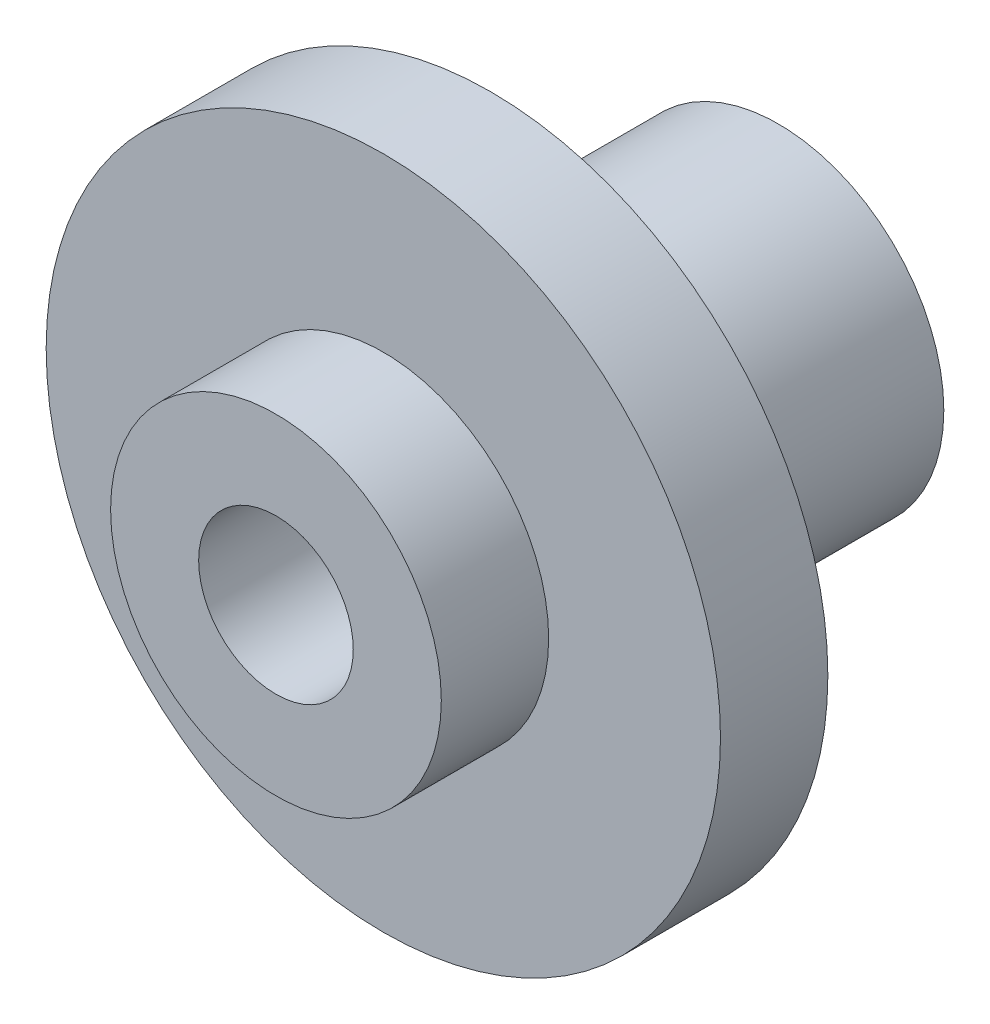
SolidWorks part; units mm, degrees
ref_plane "Front Plane" through (0, 0, 0) normal (0, 0, 1) x (1, 0, 0)
ref_plane "Top Plane" through (0, 0, 0) normal (0, 1, 0) x (1, 0, 0)
ref_plane "Right Plane" through (0, 0, 0) normal (1, 0, 0) x (0, 0, -1)
sketch "Sketch1" plane through (0, 0, 0) normal (0, 0, 1) x (1, 0, 0)
  circle A0 centre (0, 0) radius 3.9878
  dimension "D1" = 7.9756
extrude "Boss-Extrude1" add sketch "Sketch1" along normal blind 1.27
sketch "Sketch2" plane through (0, 0, 1.27) normal (0, 0, 1) x (1, 0, 0)
  circle A0 centre (0, 0) radius 1.9558
  circle A1 centre (0, 0) radius 0.9144
  dimension "D1" = 3.9116
  dimension "D2" = 1.8288
extrude "Boss-Extrude2" add sketch "Sketch2" along normal blind 1.27
sketch "Sketch3" plane through (0, 0, 0) normal (0, 0, -1) x (-1, 0, 0)
  circle A0 centre (0, 0) radius 1.9558
  dimension "D1" = 3.9116
extrude "Boss-Extrude3" add sketch "Sketch3" along normal blind 3.4036
sketch "Sketch4" plane through (0, 0, -3.4036) normal (0, 0, -1) x (-1, 0, 0)
  circle A0 centre (0, 0) radius 0.9144
  dimension "D1" = 1.8288
extrude "Cut-Extrude1" cut sketch "Sketch4" against normal through all
sketch "Sketch5" plane through (0, 0, -3.4036) normal (0, 0, -1) x (-1, 0, 0)
  line L0 (-7.2672, -0.7171) -> (-8.5589, -23.4388) construction
  line L1 (0, 0) -> (-14.5344, -1.4342) construction
  circle A0 centre (0, 0) radius 4.3688
  circle A1 centre (0, 0) radius 1.9558 construction
  dimension "D1" = 8.7376
